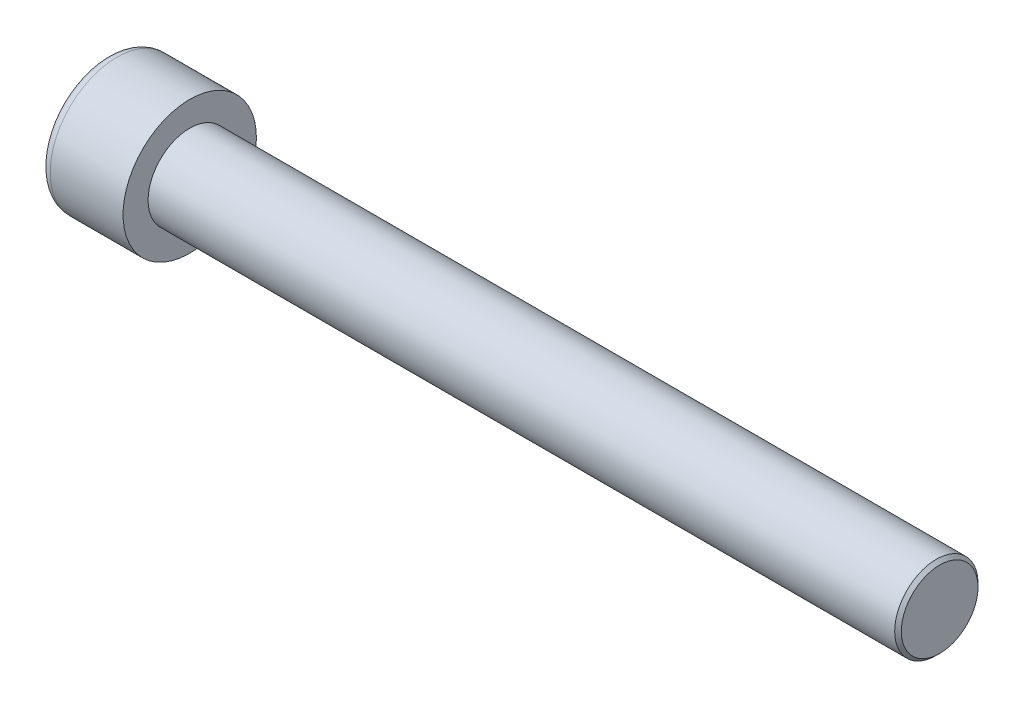
SolidWorks part; units mm, degrees
ref_plane "Front" through (0, 0, 0) normal (0, 0, 1) x (1, 0, 0)
ref_plane "Top" through (0, 0, 0) normal (0, 1, 0) x (1, 0, 0)
ref_plane "Right" through (0, 0, 0) normal (1, 0, 0) x (0, 0, -1)
sketch "Sketch1" plane through (0, 0, 0) normal (1, 0, 0) x (0, 0, -1)
  circle A0 centre (0, 0) radius 8
  dimension "dk" = 16
extrude "BaseHead" add sketch "Sketch1" along normal blind 10
sketch "Sketch2" plane through (10, 0, 0) normal (1, 0, 0) x (0, 0, -1)
  circle A0 centre (0, 0) radius 5
  dimension "d" = 10
extrude "BaseBody" add sketch "Sketch2" along normal blind 90
cosmetic thread "ThreadCosmetic1" parameters "b"=32, "D2"=8.376
sketch "Sketch3" plane through (0, 0, 0) normal (1, 0, 0) x (0, 0, -1)
  line L1 (4.6188, 0) -> (2.3094, 4)
  line L2 (2.3094, 4) -> (-2.3094, 4)
  line L3 (-2.3094, 4) -> (-4.6188, 0)
  line L4 (-4.6188, 0) -> (-2.3094, -4)
  line L5 (-2.3094, -4) -> (2.3094, -4)
  line L6 (2.3094, -4) -> (4.6188, 0)
  circle A0 centre (0, 0) radius 4 construction
  dimension "s" = 8
  dimension "e" = 9.2376
extrude "HexagonSocket" cut sketch "Sketch3" along normal blind 5
sketch "Sketch4" plane through (-4.1961, 0.75, 0) normal (0, 0, 1) x (-1, 0, 0)
  line L0 (-9.1961, 4.75) -> (-11.5055, 0.75)
  line L2 (-11.5055, 0.75) -> (-9.1961, 0.75)
  line L3 (-9.1961, 0.75) -> (-9.1961, 4.75)
  line L4 (-5.0351, 0.75) -> (0.839, 0.75) construction
  line L5 (-104.1961, 0.75) -> (-14.1961, 0.75) construction
  line L6 (-14.1961, 0.75) -> (-4.1961, 0.75) construction
  dimension "m" = 60
revolve "Cut-Revolve1" cut sketch "Sketch4" angle 360 about L4
fillet "HeadFillet" [suppressed] radius 0.4
fillet "TopFillet" radius 1.25 1 edges at (0, 0, -8)
chamfer "Chamfer1" distance 0.4 angle 45 1 edges at (100, 0, -5)
sketch "Sketch5" plane through (0, 0, 0) normal (0, 0, 1) x (1, 0, 0)
  line L0 (99.6, 4.2968) -> (100.006, 5)
  line L1 (100.006, 5) -> (100.006, 5.812)
  line L2 (100.006, 5.812) -> (99.194, 5.812)
  line L3 (99.194, 5.812) -> (99.194, 5)
  line L4 (99.194, 5) -> (99.6, 4.2968)
  line L5 (0, 0) -> (7.8886, 0) construction
  line L6 (99.6, -5) -> (99.6, 5) construction
  dimension "D1" = 10
  dimension "D2" = 0.812
revolve "Cut-Revolve10" [suppressed] cut sketch "Sketch5" angle 360 about L5
pattern_linear "LPattern10" [suppressed] count 33 spacing 0.9744 along (1, 0, 0)
equation "\"r1@TopFillet\" = \"d@Sketch2\" / 8"
equation "\"D1@Chamfer1\" = \"r@HeadFillet\""
equation "\"D1@Sketch5\" = \"d@Sketch2\""
equation "\"D2@Sketch5\" =  ( \"d@Sketch2\" - \"D2@ThreadCosmetic1\" )  / 2"
equation "\"D3@LPattern10\" = \"D2@Sketch5\" * 1.2"
equation "\"D1@LPattern10\" = \"b@ThreadCosmetic1\" / \"D3@LPattern10\""
